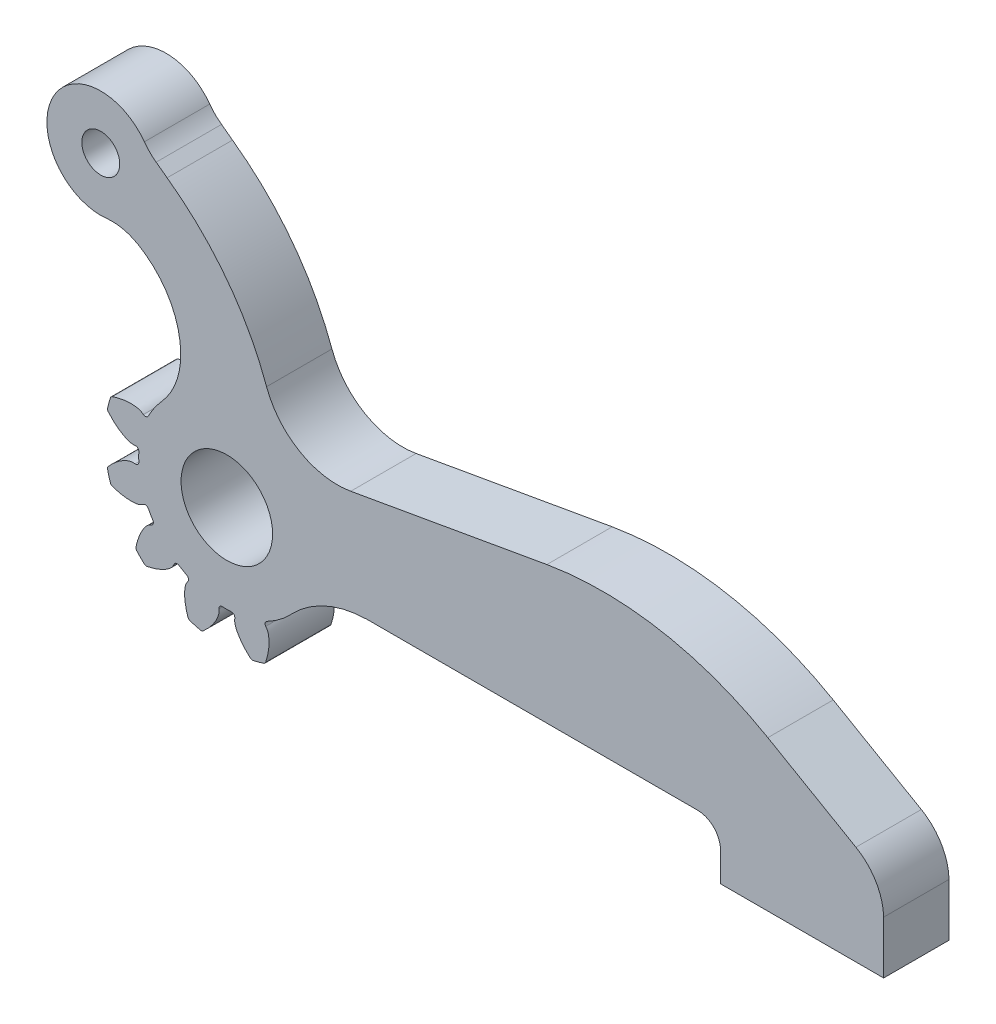
SolidWorks part; units mm, degrees
ref_plane "Plan de face" through (0, 0, 0) normal (0, 0, 1) x (1, 0, 0)
ref_plane "Plan de dessus" through (0, 0, 0) normal (0, 1, 0) x (1, 0, 0)
ref_plane "Plan de droite" through (0, 0, 0) normal (1, 0, 0) x (0, 0, -1)
sketch "Esquisse1" plane through (0, 0, 0) normal (0, 0, 1) x (1, 0, 0)
  line L0 (-23.5203, 11.0854) -> (-24.3589, 11.7065)
  line L1 (5.5245, -0.0069) -> (-9.4747, -2.6514)
  line L2 (29.1665, -6.9123) -> (22.4288, -3.0222)
  line L3 (31.2852, -14.5148) -> (31.2853, -10.4837)
  line L4 (18.8037, -14.5148) -> (31.2852, -14.5148)
  line L5 (18.8037, -12.176) -> (18.8037, -14.5148)
  line L6 (-8.2049, -10.5154) -> (17.0464, -10.5148)
  circle A0 centre (-18.9535, -8.4748) radius 3.5
  circle A1 centre (-28.5941, 10.1815) radius 1.45
  arc A2 (-22.4772, 0.0054) -> (-25.7651, 5.5736) centre (-29.046, -0.1186) ccw
  arc A3 (-25.7651, 5.5736) -> (-28.1661, 6.0838) centre (-27.7526, 2.1254) ccw
  arc A4 (-25.2604, 12.6025) -> (-28.1661, 6.0838) centre (-28.5941, 10.1815) ccw
  arc A5 (-25.2604, 12.6025) -> (-24.3589, 11.7065) centre (-22.0401, 14.9412) ccw
  arc A6 (-15.9136, 1.0533) -> (-23.5203, 11.0854) centre (-35.8813, -6.1872) ccw
  arc A7 (-15.9136, 1.0533) -> (-9.4747, -2.6514) centre (-10.4986, 3.0169) ccw
  arc A8 (22.4288, -3.0222) -> (5.5245, -0.0069) centre (9.8087, -24.8807) ccw
  arc A9 (31.2853, -10.4837) -> (29.1665, -6.9123) centre (27.0464, -10.5842) ccw
  arc A10 (18.8037, -12.176) -> (17.0464, -10.5148) centre (17.0464, -12.2748) ccw
  arc A11 (-8.2049, -10.5154) -> (-14.0364, -13.0845) centre (-8.1051, -18.6448) ccw
  arc A12 (-15.2892, -14.1317) -> (-14.0364, -13.0845) centre (-18.9535, -8.4748) ccw
  arc A13 (-15.8867, -14.4767) -> (-15.2892, -14.1317) centre (-18.9535, -8.4748) ccw
  arc A14 (-15.8867, -14.4767) -> (-15.976, -14.853) centre (-15.7712, -14.7028) ccw
  arc A15 (-16.1386, -17.3805) -> (-15.9838, -17.2291) centre (-16.2109, -17.1517) ccw
  arc A16 (-16.9386, -17.5949) -> (-16.1386, -17.3805) centre (-18.9535, -8.4748) ccw
  arc A17 (-17.1484, -17.5411) -> (-16.9386, -17.5949) centre (-16.9903, -17.3605) ccw
  arc A18 (-18.3431, -15.4873) -> (-18.6086, -15.206) centre (-18.5956, -15.4596) ccw
  arc A19 (-19.2985, -15.206) -> (-18.6086, -15.206) centre (-18.9535, -8.4748) ccw
  arc A20 (-19.2985, -15.206) -> (-19.564, -15.4873) centre (-19.3115, -15.4596) ccw
  arc A21 (-20.9686, -17.5949) -> (-20.7588, -17.5411) centre (-20.9168, -17.3605) ccw
  arc A22 (-21.7685, -17.3805) -> (-20.9686, -17.5949) centre (-18.9535, -8.4748) ccw
  arc A23 (-21.9234, -17.229) -> (-21.7685, -17.3805) centre (-21.6962, -17.1517) ccw
  arc A24 (-21.9311, -14.853) -> (-22.0204, -14.4766) centre (-22.136, -14.7028) ccw
  arc A25 (-22.6179, -14.1317) -> (-22.0204, -14.4766) centre (-18.9535, -8.4748) ccw
  arc A26 (-22.6179, -14.1317) -> (-22.9885, -14.2425) centre (-22.756, -14.3449) ccw
  arc A27 (-25.2586, -15.3655) -> (-25.0501, -15.4239) centre (-25.0966, -15.1884) ccw
  arc A28 (-25.8442, -14.7799) -> (-25.2586, -15.3655) centre (-18.9535, -8.4748) ccw
  arc A29 (-25.9026, -14.5713) -> (-25.8442, -14.7799) centre (-25.6672, -14.6179) ccw
  arc A30 (-24.7213, -12.5097) -> (-24.6104, -12.1391) centre (-24.8236, -12.2772) ccw
  arc A31 (-24.9554, -11.5416) -> (-24.6104, -12.1391) centre (-18.9535, -8.4748) ccw
  arc A32 (-24.9554, -11.5416) -> (-25.3317, -11.4523) centre (-25.1816, -11.6572) ccw
  arc A33 (-27.8593, -11.2898) -> (-27.7078, -11.4446) centre (-27.6304, -11.2174) ccw
  arc A34 (-28.0736, -10.4898) -> (-27.8593, -11.2898) centre (-18.9535, -8.4748) ccw
  arc A35 (-28.0199, -10.28) -> (-28.0736, -10.4898) centre (-27.8393, -10.438) ccw
  arc A36 (-25.966, -9.0852) -> (-25.6847, -8.8198) centre (-25.9384, -8.8328) ccw
  arc A37 (-25.6847, -8.1298) -> (-25.6847, -8.8198) centre (-18.9535, -8.4748) ccw
  arc A38 (-25.6847, -8.1298) -> (-25.966, -7.8643) centre (-25.9384, -8.1168) ccw
  arc A39 (-28.0736, -6.4598) -> (-28.0198, -6.6696) centre (-27.8392, -6.5115) ccw
  arc A40 (-27.8592, -5.6598) -> (-28.0736, -6.4598) centre (-18.9535, -8.4748) ccw
  arc A41 (-27.7078, -5.505) -> (-27.8592, -5.6598) centre (-27.6304, -5.7322) ccw
  arc A42 (-25.3317, -5.4972) -> (-24.9554, -5.408) centre (-25.1816, -5.2924) ccw
  arc A43 (-23.9587, -3.9609) -> (-24.9554, -5.408) centre (-18.9535, -8.4748) ccw
  arc A44 (-23.9587, -3.9609) -> (-22.4772, 0.0054) centre (-28.2362, -0.1033) ccw
  spline S0 degree 3 poles (-15.976, -14.853) (-15.8583, -15.0136) (-15.8123, -15.1379) (-15.7604, -15.3337) (-15.7501, -15.4193) (-15.7322, -15.5871) (-15.7279, -15.6662) (-15.7227, -15.9176) (-15.7338, -16.0785) (-15.7702, -16.3892) (-15.7966, -16.5374) (-15.871, -16.8708) (-15.9236, -17.0525) (-15.9838, -17.2291) knots 0 0 0 0 0.081188 0.081188 0.177126 0.177126 0.273064 0.273064 0.491379 0.491379 0.709693 0.709693 1 1 1 1
  spline S1 degree 3 poles (-17.1484, -17.5411) (-17.3424, -17.3713) (-17.5292, -17.185) (-17.7642, -16.9031) (-17.8213, -16.8306) (-17.9892, -16.6) (-18.0954, -16.4357) (-18.2194, -16.1741) (-18.2466, -16.113) (-18.2916, -15.9918) (-18.311, -15.9377) (-18.3444, -15.798) (-18.3566, -15.707) (-18.3494, -15.5543) (-18.3469, -15.5218) (-18.3431, -15.4873) knots 0 0 0 0 0.40138 0.40138 0.532597 0.532597 0.795032 0.795032 0.872293 0.872293 0.929035 0.929035 0.985778 0.985778 1 1 1 1
  spline S2 degree 3 poles (-19.564, -15.4873) (-19.5424, -15.6852) (-19.5647, -15.8159) (-19.6177, -16.0114) (-19.6516, -16.0906) (-19.7199, -16.2449) (-19.7558, -16.3155) (-19.8769, -16.5359) (-19.967, -16.6697) (-20.1539, -16.9206) (-20.2509, -17.0357) (-20.482, -17.2872) (-20.6184, -17.4182) (-20.7588, -17.5411) knots 0 0 0 0 0.081188 0.081188 0.177126 0.177126 0.273064 0.273064 0.491379 0.491379 0.709693 0.709693 1 1 1 1
  spline S3 degree 3 poles (-21.9234, -17.229) (-22.0065, -16.985) (-22.0751, -16.7302) (-22.1377, -16.3686) (-22.1508, -16.2773) (-22.1809, -15.9936) (-22.1908, -15.7982) (-22.1674, -15.5097) (-22.1604, -15.4431) (-22.1388, -15.3157) (-22.1285, -15.2592) (-22.0876, -15.1214) (-22.0527, -15.0365) (-21.9701, -14.9079) (-21.9517, -14.881) (-21.9311, -14.853) knots 0 0 0 0 0.40138 0.40138 0.532597 0.532597 0.795032 0.795032 0.872293 0.872293 0.929035 0.929035 0.985778 0.985778 1 1 1 1
  spline S4 degree 3 poles (-22.9885, -14.2425) (-23.0687, -14.4248) (-23.1533, -14.5268) (-23.297, -14.6696) (-23.3659, -14.7213) (-23.5023, -14.8207) (-23.5687, -14.864) (-23.7838, -14.9942) (-23.9286, -15.065) (-24.2159, -15.1889) (-24.3575, -15.2401) (-24.6834, -15.3423) (-24.867, -15.3876) (-25.0501, -15.4239) knots 0 0 0 0 0.081188 0.081188 0.177126 0.177126 0.273064 0.273064 0.491379 0.491379 0.709693 0.709693 1 1 1 1
  spline S5 degree 3 poles (-25.9026, -14.5713) (-25.8526, -14.3184) (-25.7846, -14.0634) (-25.658, -13.7189) (-25.6237, -13.6333) (-25.508, -13.3726) (-25.4188, -13.1984) (-25.2543, -12.9603) (-25.2149, -12.9061) (-25.1325, -12.8066) (-25.0953, -12.7627) (-24.991, -12.664) (-24.9183, -12.6079) (-24.7825, -12.5378) (-24.7531, -12.5237) (-24.7213, -12.5097) knots 0 0 0 0 0.40138 0.40138 0.532597 0.532597 0.795032 0.795032 0.872293 0.872293 0.929035 0.929035 0.985778 0.985778 1 1 1 1
  spline S6 degree 3 poles (-25.3317, -11.4523) (-25.4923, -11.5701) (-25.6167, -11.6161) (-25.8125, -11.668) (-25.898, -11.6782) (-26.0658, -11.6961) (-26.1449, -11.7004) (-26.3963, -11.7057) (-26.5572, -11.6946) (-26.8679, -11.6582) (-27.0162, -11.6317) (-27.3495, -11.5573) (-27.5312, -11.5048) (-27.7078, -11.4446) knots 0 0 0 0 0.081188 0.081188 0.177126 0.177126 0.273064 0.273064 0.491379 0.491379 0.709693 0.709693 1 1 1 1
  spline S7 degree 3 poles (-28.0199, -10.28) (-27.8501, -10.086) (-27.6637, -9.8991) (-27.3818, -9.6641) (-27.3093, -9.6071) (-27.0787, -9.4392) (-26.9144, -9.3329) (-26.6529, -9.209) (-26.5917, -9.1818) (-26.4706, -9.1368) (-26.4165, -9.1174) (-26.2767, -9.084) (-26.1857, -9.0718) (-26.0331, -9.0789) (-26.0006, -9.0815) (-25.966, -9.0852) knots 0 0 0 0 0.40138 0.40138 0.532597 0.532597 0.795032 0.795032 0.872293 0.872293 0.929035 0.929035 0.985778 0.985778 1 1 1 1
  spline S8 degree 3 poles (-25.966, -7.8643) (-26.1639, -7.886) (-26.2946, -7.8637) (-26.4901, -7.8107) (-26.5693, -7.7768) (-26.7236, -7.7084) (-26.7943, -7.6726) (-27.0146, -7.5514) (-27.1484, -7.4614) (-27.3993, -7.2745) (-27.5144, -7.1775) (-27.7659, -6.9464) (-27.897, -6.81) (-28.0198, -6.6696) knots 0 0 0 0 0.081188 0.081188 0.177126 0.177126 0.273064 0.273064 0.491379 0.491379 0.709693 0.709693 1 1 1 1
  spline S9 degree 3 poles (-27.7078, -5.505) (-27.4638, -5.4219) (-27.209, -5.3532) (-26.8473, -5.2906) (-26.756, -5.2775) (-26.4723, -5.2474) (-26.2769, -5.2375) (-25.9884, -5.261) (-25.9218, -5.268) (-25.7945, -5.2896) (-25.7379, -5.2998) (-25.6002, -5.3408) (-25.5153, -5.3757) (-25.3867, -5.4582) (-25.3598, -5.4767) (-25.3317, -5.4972) knots 0 0 0 0 0.40138 0.40138 0.532597 0.532597 0.795032 0.795032 0.872293 0.872293 0.929035 0.929035 0.985778 0.985778 1 1 1 1
  dimension "D1" = 7
  dimension "D2" = 21.24
  dimension "D3" = 25.24
  dimension "D4" = 4.24
  dimension "D5" = 1.76
  dimension "D6" = 8.13
  dimension "D7" = 6.57
  dimension "D8" = 3.98
  dimension "D9" = 2.9
  dimension "D10" = 4.12
  dimension "D11" = 5.76
  dimension "D12" = 6.74
  dimension "D13" = 5.76
  dimension "D14" = 3.98
extrude "Boss.-Extru.1" add sketch "Esquisse1" along normal blind 5
